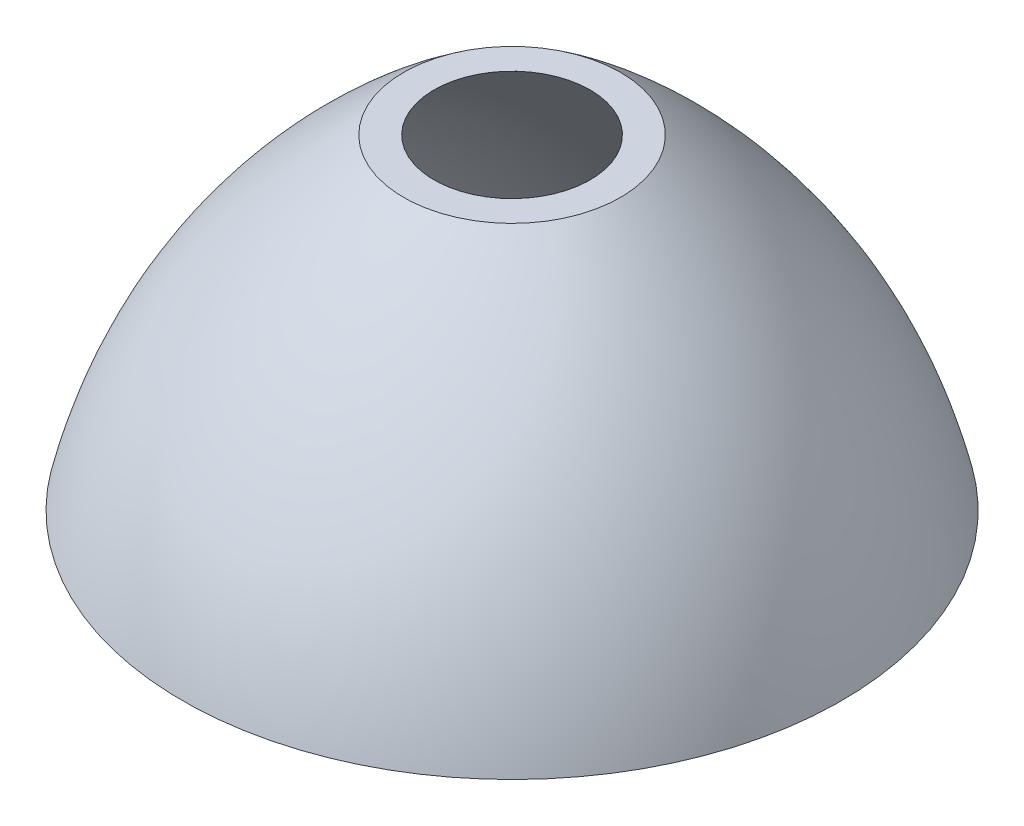
SolidWorks part; units mm, degrees
material "Acrylic (Medium-high impact)"
ref_plane "Front Plane" through (0, 0, 0) normal (0, 0, 1) x (1, 0, 0)
ref_plane "Top Plane" through (0, 0, 0) normal (0, 1, 0) x (1, 0, 0)
ref_plane "Right Plane" through (0, 0, 0) normal (1, 0, 0) x (0, 0, -1)
sketch "Sketch1" plane through (0, 0, 0) normal (0, 0, 1) x (1, 0, 0)
  line L0 (-75, 0) -> (75, 0)
  line L1 (0, 0) -> (0, 75)
  line L2 (-16, 75) -> (16, 75)
  line L3 (0, 75) -> (0, 115)
  line L4 (-11.5, 115) -> (11.5, 115)
  line L5 (-18, 115) -> (-14.75, 115)
  line L6 (18, 115) -> (14.75, 115)
  line L7 (-75, 0) -> (-73, 0)
  line L8 (14.75, 115) -> (14.75, 113.2)
  line L9 (-18, 75) -> (-18, 115)
  line L10 (-16, 75) -> (-16, 112)
  line L11 (-14.75, 115) -> (-14.75, 113.2)
  line L12 (-14.95, 113) -> (-15, 113)
  line L13 (14.95, 113) -> (15, 113)
  line L14 (16, 75) -> (16, 112)
  line L15 (18, 75) -> (18, 115)
  line L16 (-18, 115) -> (-25, 115)
  line L17 (-18, 75) -> (-25, 75)
  line L18 (-25, 75) -> (-25, 115)
  line L19 (-75, 0) -> (-76, 0)
  line L20 (75, 0) -> (76, 0)
  line L21 (18, 115) -> (25, 115)
  line L22 (25, 75) -> (25, 115)
  line L23 (18, 75) -> (25, 75)
  arc A0 (-15, 113) -> (-16, 112) centre (-15, 112) ccw
  arc A1 (-14.75, 113.2) -> (-14.95, 113) centre (-14.95, 113.2) cw
  arc A2 (14.75, 113.2) -> (14.95, 113) centre (14.95, 113.2) ccw
  arc A3 (15, 113) -> (16, 112) centre (15, 112) cw
  spline S0 degree 2 poles (-75, 0) (-58.4063, 46.597) (-18, 75) knots 0 0 0 1 1 1
  spline S1 degree 2 poles (-73, 0) (-55.204, 45.6046) (-16, 75) knots 0 0 0 1 1 1
  spline S2 degree 2 poles (75, 0) (58.4063, 46.597) (18, 75) knots 0 0 0 1 1 1
  spline S3 degree 2 poles (73, 0) (55.204, 45.6046) (16, 75) knots 0 0 0 1 1 1
  spline S4 degree 2 poles (-76, 0) (-65.368, 45.3534) (-25, 75) knots 0 0 0 1 1 1
  spline S5 degree 2 poles (76, 0) (65.368, 45.3534) (25, 75) knots 0 0 0 1 1 1
  point P4 (0, 0)
  point P10 (0, 75)
  point P14 (0, 115)
  dimension "D1" = 1
  dimension "D2" = 0.2
revolve "Revolve1" add sketch "Sketch1" angle 360 about L1
